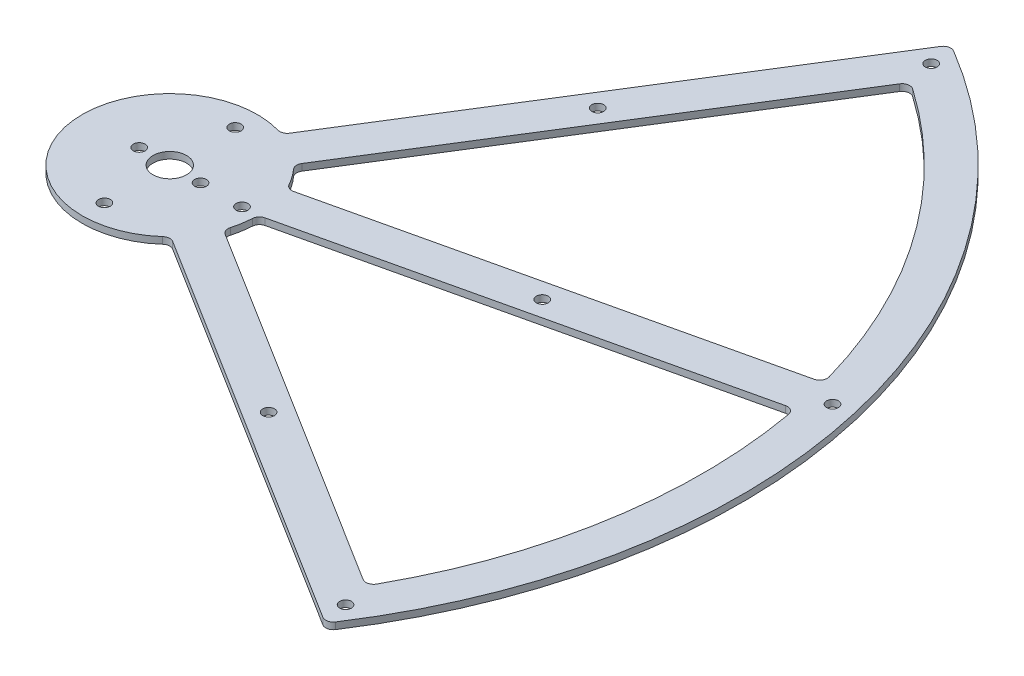
SolidWorks part; units mm, degrees
material "Zoltek Panex 33"
ref_plane "Front Plane" through (0, 0, 0) normal (0, 0, 1) x (1, 0, 0)
ref_plane "Top Plane" through (0, 0, 0) normal (0, 1, 0) x (1, 0, 0)
ref_plane "Right Plane" through (0, 0, 0) normal (1, 0, 0) x (0, 0, -1)
sketch "Sketch1" plane through (0, 0, 0) normal (0, 1, 0) x (1, 0, 0)
  line L0 (0, 0) -> (146.1555, 33.7427) construction
  line L1 (0, 0) -> (79.4879, 127.2072) construction
  line L2 (0, 0) -> (127.2072, -79.4879) construction
  line L3 (22.2601, 10.2707) -> (133.1652, 35.8751)
  line L4 (24.5096, 0.527) -> (135.4147, 26.1314)
  line L5 (16.9583, 17.7036) -> (77.275, 114.2304)
  line L6 (8.4778, 23.0028) -> (74.1717, 128.1349)
  line L7 (23.0028, -8.4778) -> (119.5296, -68.7945)
  line L8 (17.7036, -16.9583) -> (122.8357, -82.6522)
  line L9 (0, 0) -> (88.5062, 0) construction
  arc A0 (6.2392, 22.1376) -> (15.3122, -17.162) centre (0, 0) ccw
  arc A1 (134.6387, 38.372) -> (80.1156, 114.8107) centre (0, 0) ccw
  arc A2 (125.5698, -82.0501) -> (76.893, 128.7923) centre (0, 0) ccw
  arc A3 (20.0654, 11.2419) -> (17.162, 15.3122) centre (0, 0) ccw
  arc A4 (22.1376, -6.2392) -> (22.9628, -1.308) centre (0, 0) ccw
  arc A5 (122.3371, -68.0708) -> (137.8337, 24.5332) centre (0, 0) ccw
  arc A6 (122.8357, -82.6522) -> (125.5698, -82.0501) centre (123.8956, -80.9561) ccw
  arc A7 (17.7036, -16.9583) -> (15.3122, -17.162) centre (16.6437, -18.6544) ccw
  arc A8 (119.5296, -68.7945) -> (122.3371, -68.0708) centre (120.5894, -67.0984) ccw
  arc A9 (23.0028, -8.4778) -> (22.1376, -6.2392) centre (24.0626, -6.7817) cw
  arc A10 (74.1717, 128.1349) -> (76.893, 128.7923) centre (75.8678, 127.0751) cw
  arc A11 (8.4778, 23.0028) -> (6.2392, 22.1376) centre (6.7817, 24.0626) cw
  arc A12 (77.275, 114.2304) -> (80.1156, 114.8107) centre (78.9711, 113.1705) cw
  arc A13 (135.4147, 26.1314) -> (137.8337, 24.5332) centre (135.8646, 24.1827) cw
  arc A14 (24.5096, 0.527) -> (22.9628, -1.308) centre (24.9595, -1.4218) ccw
  arc A15 (133.1652, 35.8751) -> (134.6387, 38.372) centre (132.7153, 37.8239) ccw
  arc A16 (16.9583, 17.7036) -> (17.162, 15.3122) centre (18.6544, 16.6437) ccw
  arc A17 (22.2601, 10.2707) -> (20.0654, 11.2419) centre (21.8102, 12.2194) cw
  point P25 (21.6882, -7.6564)
  point P27 (0.001, 0)
  point P43 (20.7498, 9.922)
  dimension "D1" = 10
  dimension "D10" = 23
  dimension "D11" = 140
  dimension "D12" = 2
  dimension "D2" = 10
  dimension "D3" = 45
  dimension "D4" = 5
  dimension "D5" = 45
  dimension "D6" = 5
  dimension "D7" = 10
  dimension "D8" = 5
  dimension "D9" = 10
  dimension "D13" = 32
extrude "Boss-Extrude1" add sketch "Sketch1" along normal blind 1.75
sketch "Sketch2" plane through (0, 1.75, 0) normal (0, 1, 0) x (1, 0, 0)
  line L0 (0, 0) -> (85.7967, 137.3034) construction
  line L1 (0, 0) -> (175.3344, 40.4791) construction
  line L2 (0, 0) -> (150.2013, -93.8562) construction
  line L3 (23.0028, -8.4778) -> (119.5296, -68.7945) construction
  line L4 (22.2601, 10.2707) -> (133.1652, 35.8751) construction
  line L5 (77.275, 114.2304) -> (16.9583, 17.7036) construction
  circle A0 centre (0, 0) radius 4.4
  circle A1 centre (8.0648, 0) radius 1.55
  circle A2 centre (18.95, 0) radius 1.55
  circle A3 centre (-8.0352, 0) radius 1.55
  circle A4 centre (0.0148, 17.15) radius 1.55
  circle A5 centre (-0.0148, -17.15) radius 1.55
  circle A6 centre (69.1159, -43.1884) radius 1.55
  circle A7 centre (122.967, -76.8383) radius 1.55
  circle A8 centre (141.2837, 32.6179) radius 1.55
  circle A9 centre (79.4112, 18.3335) radius 1.55
  circle A10 centre (43.1884, 69.1159) radius 1.55
  circle A11 centre (76.8383, 122.967) radius 1.55
  point P12 (0.0148, 0)
  point P16 (0, 0)
  dimension "D1" = 2
  dimension "D2" = 16.1
  dimension "D3" = 18.95
  dimension "D4" = 2
  dimension "D5" = 17.15
  dimension "D6" = 81.5
  dimension "D7" = 81.5
  dimension "D8" = 81.5
  dimension "D9" = 145
  dimension "D10" = 145
  dimension "D11" = 145
extrude "Mounting_Holes" cut sketch "Sketch2" against normal up to next
equation "\"d1\"= 1cm"
equation "\"D2@Sketch1\"=\"d1\""
equation "\"D4@Sketch1\"=\"d1\"/2"
equation "\"D6@Sketch1\"=\"d1\"/2"
equation "\"D7@Sketch1\"=\"d1\""
equation "\"D8@Sketch1\"=\"d1\"/2"
equation "\"D9@Sketch1\"=\"d1\""
equation "\"D1@Sketch1\"=\"d1\""
equation "\"r1\"= 23mm"
equation "\"r2\"= 14cm"
equation "\"D11@Sketch1\"=\"r2\""
equation "\"D10@Sketch1\"=\"r1\""
equation "\"D3@Sketch2\"=13+4.4+1.55"
equation "\"D5@Sketch2\"=11.2+4.4+1.55"
equation "\"D5@Sketch1\"=\"D3@Sketch1\""
equation "\"D6@Sketch2\"=(\"r2\"+\"r1\")/2"
equation "\"D7@Sketch2\"=\"D6@Sketch2\""
equation "\"D8@Sketch2\"=\"D6@Sketch2\""
equation "\"D9@Sketch2\"=\"r2\"+\"d1\"/2"
equation "\"D10@Sketch2\"=\"D9@Sketch2\""
equation "\"D11@Sketch2\"=\"D9@Sketch2\""
